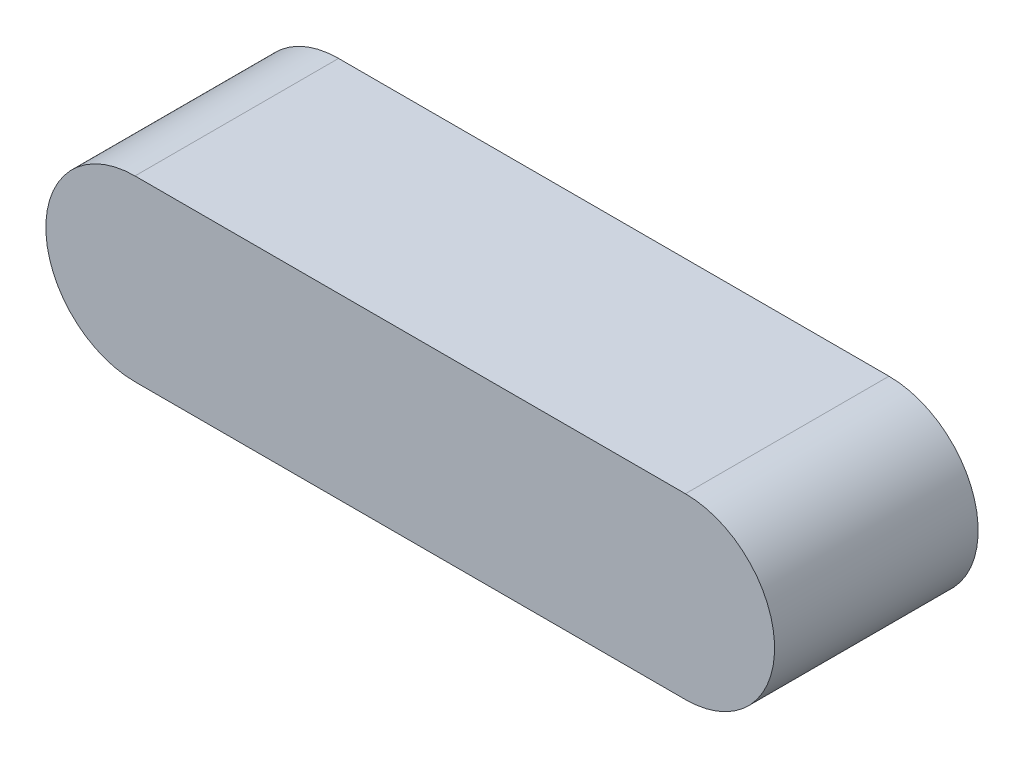
SolidWorks part; units mm, degrees
ref_plane "Front Plane" through (0, 0, 0) normal (0, 0, 1) x (1, 0, 0)
ref_plane "Top Plane" through (0, 0, 0) normal (0, 1, 0) x (1, 0, 0)
ref_plane "Right Plane" through (0, 0, 0) normal (1, 0, 0) x (0, 0, -1)
sketch "CurveSketch" plane through (0, 0, 0) normal (0, 0, 1) x (1, 0, 0)
  line L0 (-8.6665, -18.856) -> (23.0525, -18.856)
  line L1 (23.0525, -8.582) -> (-8.6665, -8.582)
  arc A0 (-8.6665, -8.582) -> (-8.6665, -18.856) centre (-8.6665, -13.719) ccw
  arc A1 (23.0525, -18.856) -> (23.0525, -8.582) centre (23.0525, -13.719) ccw
  dimension "D1" = 5.137
extrude "CurveBoss" add sketch "CurveSketch" along normal blind 11.731
